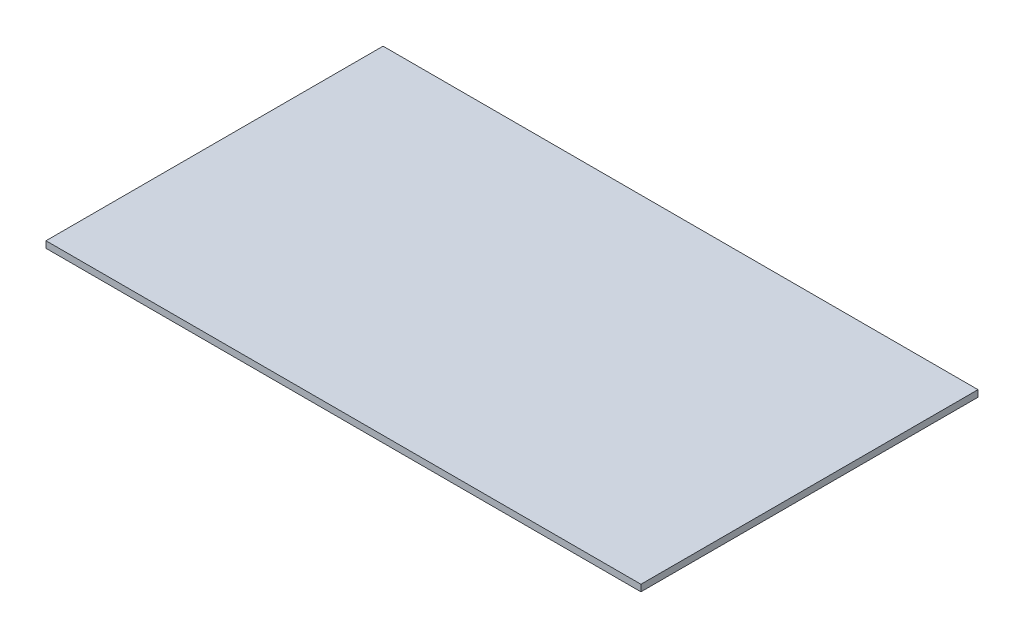
SolidWorks part; units mm, degrees
material "ABS PC"
ref_plane "X-Y Datum" through (0, 0, 0) normal (0, 0, 1) x (1, 0, 0)
ref_plane "X-Z Datum" through (0, 0, 0) normal (0, 1, 0) x (1, 0, 0)
ref_plane "Y-Z Datum" through (0, 0, 0) normal (1, 0, 0) x (0, 0, -1)
sketch "Sketch1" plane through (0, 0, 0) normal (0, 0, 1) x (1, 0, 0)
  line L1 (-143.1811, -1.5875) -> (143.1811, -1.5875)
  line L2 (-143.1811, -1.5875) -> (-143.1811, 1.5875)
  line L3 (-143.1811, 1.5875) -> (143.1811, 1.5875)
  line L4 (143.1811, -1.5875) -> (143.1811, 1.5875)
  line L5 (-143.1811, -1.5875) -> (143.1811, 1.5875) construction
  line L6 (-143.1811, 1.5875) -> (143.1811, -1.5875) construction
  point P0 (0, 0)
  dimension "D1" = 286.3621
  dimension "D2" = 3.175
extrude "Boss-Extrude1" add sketch "Sketch1" along normal blind 162.2323
